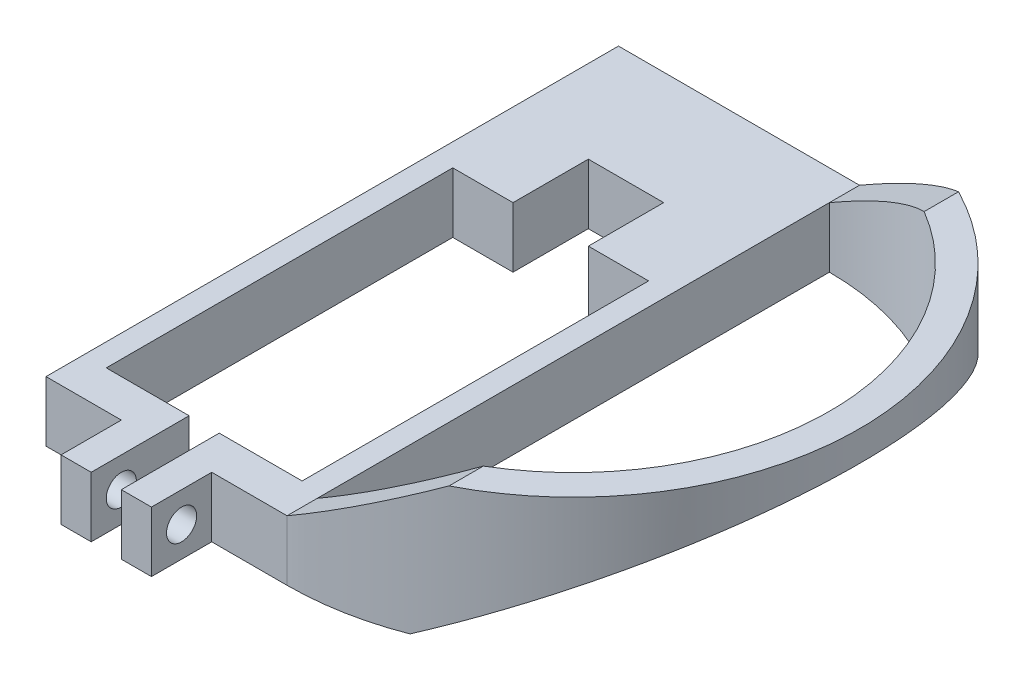
SolidWorks part; units mm, degrees
ref_plane "前视基准面" through (0, 0, 0) normal (0, 0, 1) x (1, 0, 0)
ref_plane "上视基准面" through (0, 0, 0) normal (0, 1, 0) x (1, 0, 0)
ref_plane "右视基准面" through (0, 0, 0) normal (1, 0, 0) x (0, 0, -1)
sketch "Sketch1" plane through (0, 0, 0) normal (0, 1, 0) x (1, 0, 0)
  line L0 (0, 0) -> (0, -5) construction
  line L1 (-8, -19) -> (8, -19)
  line L2 (-8, -19) -> (-8, 19)
  line L3 (-8, 19) -> (8, 19)
  line L4 (8, -19) -> (8, 19) construction
  line L5 (-8, -19) -> (8, 19) construction
  line L6 (-8, 19) -> (8, -19) construction
  line L7 (8, 17) -> (8, -17)
  line L8 (-6.5, -16.5) -> (6.5, -16.5)
  line L9 (-6.5, -16.5) -> (-6.5, 6.5)
  line L10 (-6.5, 6.5) -> (6.5, 6.5)
  line L11 (6.5, -16.5) -> (6.5, 6.5)
  line L12 (-6.5, -16.5) -> (6.5, 6.5) construction
  line L13 (-6.5, 6.5) -> (6.5, -16.5) construction
  arc A0 (8, 19) -> (8, -19) centre (8, 0) cw
  arc A1 (8, 17) -> (8, -17) centre (8, 0) cw
  point P0 (0, 0)
  dimension "D6" = 2
  dimension "D1" = 13
  dimension "D2" = 38
  dimension "D3" = 16
  dimension "D4" = 23
  dimension "D5" = 6.5
extrude "Boss-Extrude1" add sketch "Sketch1" along normal blind 4
sketch "Sketch2" plane through (0, 4, 0) normal (0, 1, 0) x (1, 0, 0)
  line L0 (8, 19) -> (8, 17)
  line L1 (8, -17) -> (8, -19)
  arc A0 (8, -19) -> (8, 19) centre (8, 0) ccw construction
  arc A2 (8, -17) -> (8, 17) centre (8, 0) ccw construction
  arc A3 (8, -19) -> (8, 19) centre (8, 0) ccw
  arc A4 (8, -17) -> (8, 17) centre (8, 0) ccw
extrude "Boss-Extrude2" add sketch "Sketch2" along normal blind 5
sketch "Sketch3" plane through (0, 0, 19) normal (0, 0, 1) x (1, 0, 0)
  line L0 (8, 4) -> (8, 9)
  line L1 (8, 9) -> (8, 4) construction
  line L2 (25, 9) -> (8, 9) construction
  line L3 (8, 9) -> (16.6603, 9)
  line L4 (27, 9) -> (8, 9) construction
  line L5 (16.6603, 9) -> (8, 4)
  line L6 (27, 7) -> (14.8756, 0)
  line L7 (27, 0) -> (27, 9) construction
  line L8 (8, 0) -> (27, 0) construction
  line L9 (14.8756, 0) -> (27, 0)
  line L10 (27, 0) -> (27, 7)
  dimension "D1" = 7
  dimension "D2" = 30
extrude "Cut-Extrude1" cut sketch "Sketch3" against normal up to surface (38 mm away) up to face at (0, 2, -19)
sketch "Sketch4" plane through (0, 4, 0) normal (0, 1, 0) x (1, 0, 0)
  line L0 (0, 0) -> (0, -16.5) construction
  line L1 (6.5, 6.5) -> (-6.5, 6.5) construction
  line L2 (-2.5, 6.5) -> (2.5, 6.5)
  line L3 (-2.5, 6.5) -> (-2.5, 11.5)
  line L4 (-2.5, 11.5) -> (2.5, 11.5)
  line L5 (-6.5, -16.5) -> (6.5, -16.5) construction
  line L6 (2.5, 6.5) -> (2.5, 11.5)
  line L7 (0, 0) -> (0, 6.5) construction
  line L8 (-8, -19) -> (8, -19) construction
  line L9 (-1, -16.5) -> (1, -16.5)
  line L10 (-1, -16.5) -> (-1, -19)
  line L11 (-1, -19) -> (1, -19)
  line L12 (1, -16.5) -> (1, -19)
  dimension "D1" = 5
  dimension "D2" = 5
  dimension "D3" = 2
extrude "Cut-Extrude2" cut sketch "Sketch4" against normal up to next
sketch "Sketch5" plane through (0, 0, 0) normal (0, -1, 0) x (1, 0, 0)
  line L1 (-1, 19) -> (-3, 19)
  line L2 (-1, 19) -> (-1, 23)
  line L3 (-1, 23) -> (-3, 23)
  line L4 (-3, 19) -> (-3, 23)
  dimension "D1" = 4
  dimension "D2" = 2
extrude "Boss-Extrude3" add sketch "Sketch5" against normal up to surface (4 mm away) up to face at (0.8889, 4, 3.0556)
sketch "Sketch6" plane through (-3, 0, 0) normal (-1, 0, 0) x (0, 0, 1)
  line L0 (21, 2) -> (23, 2) construction
  line L1 (23, 4) -> (23, 0) construction
  circle A0 centre (21, 2) radius 1
  dimension "D1" = 2
  dimension "D2" = 2
extrude "Cut-Extrude3" cut sketch "Sketch6" against normal up to next
mirror "Mirror1" about plane through (0, 0, 0) normal (1, 0, 0) of "Cut-Extrude3", "Boss-Extrude3"
